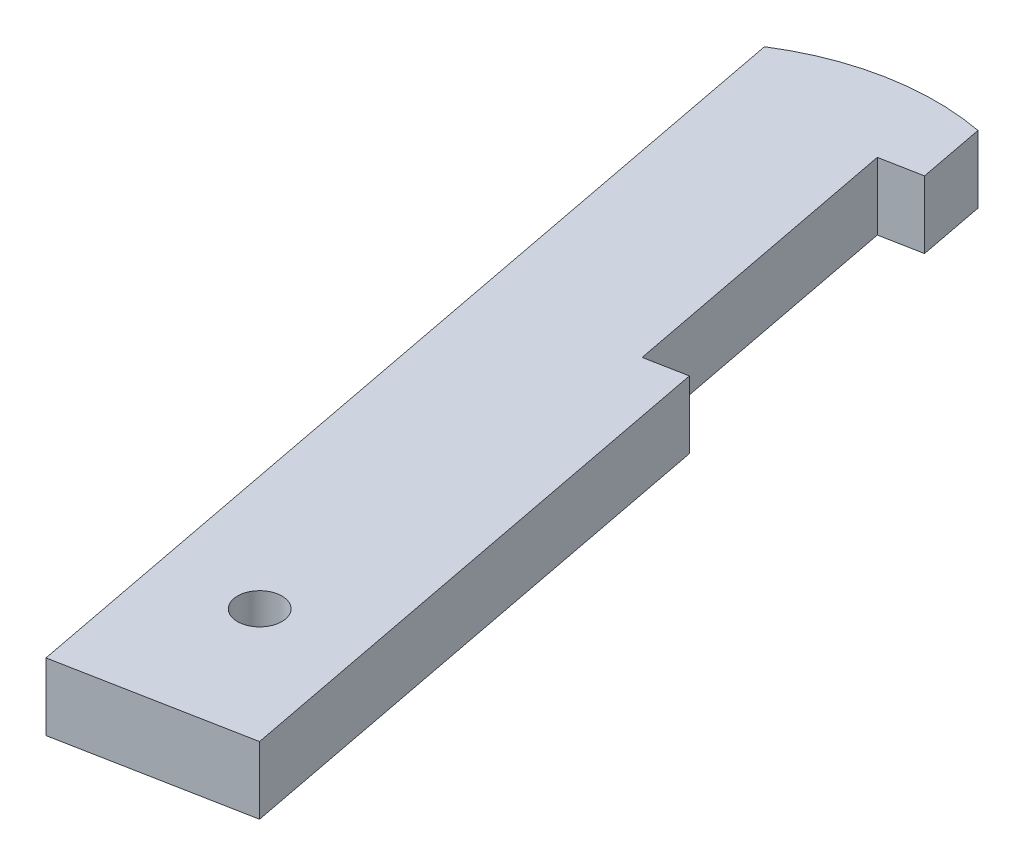
SolidWorks part; units mm, degrees
ref_plane "Front Plane" through (0, 0, 0) normal (0, 0, 1) x (1, 0, 0)
ref_plane "Top Plane" through (0, 0, 0) normal (0, 1, 0) x (1, 0, 0)
ref_plane "Right Plane" through (0, 0, 0) normal (1, 0, 0) x (0, 0, -1)
sketch "Sketch1" plane through (0, 0, 0) normal (0, 1, 0) x (1, 0, 0)
  line L0 (0, 0) -> (0, 50000) construction
  line L1 (-3.4777, 18.1702) -> (18.5162, -96.744) construction
  line L2 (-9.8948, 15.6315) -> (2.7399, -50.3831)
  line L3 (8.4989, -8.3382) -> (16.0582, -47.8341)
  line L4 (2.7399, -50.3831) -> (16.0582, -47.8341)
  line L5 (3.4234, 18.1805) -> (4.3633, 13.2696)
  line L6 (1.4168, 12.7057) -> (5.5524, -8.9021)
  line L7 (5.5524, -8.9021) -> (8.4989, -8.3382)
  line L8 (4.3633, 13.2696) -> (1.4168, 12.7057)
  arc A0 (0, -18.5) -> (-3.4234, -18.1805) centre (0, 0) ccw construction
  arc A1 (3.4234, 18.1805) -> (-9.8948, 15.6315) centre (0, 0) ccw
  circle A2 centre (7.5193, -39.2869) radius 1.65
  point P11 (7.5193, -39.2869)
  dimension "D1" = 37
  dimension "D6" = 3.3
  dimension "D2" = 13.56
  dimension "D3" = 40
  dimension "D4" = 10
  dimension "D5" = 10.835
  dimension "D7" = 5
  dimension "D8" = 3
  dimension "D9" = 22
extrude "Boss-Extrude1" add sketch "Sketch1" along normal blind 5
